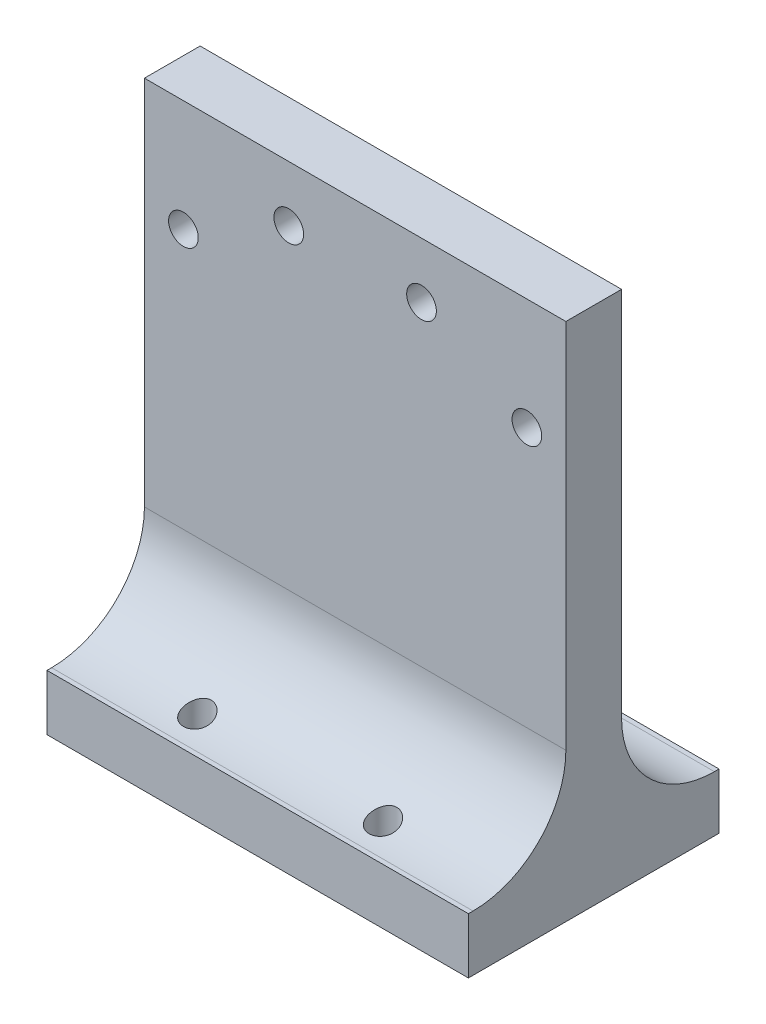
SolidWorks part; units mm, degrees
ref_plane "Płaszczyzna przednia" through (0, 0, 0) normal (0, 0, 1) x (1, 0, 0)
ref_plane "Płaszczyzna górna" through (0, 0, 0) normal (0, 1, 0) x (1, 0, 0)
ref_plane "Płaszczyzna prawa" through (0, 0, 0) normal (1, 0, 0) x (0, 0, -1)
sketch "Sketch1" plane through (0, 0, 0) normal (0, 1, 0) x (1, 0, 0)
  line L1 (0, 0) -> (45.4, 0)
  line L2 (0, 0) -> (0, 27)
  line L3 (0, 27) -> (45.4, 27)
  line L4 (45.4, 0) -> (45.4, 27)
  dimension "D1" = 45.4
  dimension "D2" = 27
extrude "Boss-Extrude1" add sketch "Sketch1" along normal blind 6
sketch "Sketch4" plane through (0, 6, 0) normal (0, 1, 0) x (1, 0, 0)
  line L0 (0, 27) -> (0, 0) construction
  line L1 (0, 16.5) -> (45.4, 16.5)
  line L2 (0, 16.5) -> (0, 10.5)
  line L3 (0, 10.5) -> (45.4, 10.5)
  line L4 (45.4, 16.5) -> (45.4, 10.5)
  line L5 (45.4, 0) -> (45.4, 27) construction
  line L6 (0, 0) -> (45.4, 0) construction
  dimension "D1" = 6
  dimension "D2" = 10.5
extrude "Boss-Extrude2" add sketch "Sketch4" along normal blind 50
fillet "Fillet3" radius 10 2 edges at (22.7, 6, -10.5) (22.7, 6, -16.5)
ref_plane "Plane3" through (0, 16, 0) normal (0, -1, 0) x (-1, 0, 0)
hole_wizard "Ø3.0mm Dowel Hole1" positions "Sketch2" profile "Sketch3" hole size "Ø3.0" standard "ANSI Metric" end condition up to next
sketch "Sketch2" plane through (0, 16, 0) normal (0, 1, 0) x (1, 0, 0)
  point P0 (12.7, 23.5)
  point P2 (32.7, 23.5)
  point P4 (32.7, 3.5)
  point P6 (12.7, 3.5)
  dimension "D1" = 20
  dimension "D2" = 20
  dimension "D3" = 20
sketch "Sketch3" plane through (12.7, 16, -23.5) normal (1, 0, 0) x (0, 0, 1)
  line L0 (0, 0) -> (0, 16)
  line L1 (0, 16) -> (1.5, 16)
  line L2 (1.5, 16) -> (1.5, 0)
  line L5 (1.5, 0) -> (0, 0)
  line L11 (0, -6.35) -> (0, 107.95) construction
  dimension "Thru Hole Dia." = 3
  dimension "Thru Hole Depth" = 16
ref_plane "Plane4" through (22.7, 0, 0) normal (1, 0, 0) x (0, 0, -1)
hole_wizard "Ø3.0mm Dowel Hole2" positions "Sketch6" profile "Sketch7" hole size "Ø3.0" standard "ANSI Metric" end condition up to next
sketch "Sketch6" plane through (0, 0, -16.5) normal (0, 0, -1) x (-1, 0, 0)
  line L2 (-45.4, 56) -> (0, 56) construction
  point P0 (-29.85, 50)
  point P2 (-15.55, 50)
  dimension "D1" = 14.3
  dimension "D3" = 6
sketch "Sketch7" plane through (29.85, 50, -16.5) normal (1, 0, 0) x (0, 1, 0)
  line L0 (0, 0) -> (0, 6)
  line L1 (0, 6) -> (1.6, 6)
  line L2 (1.6, 6) -> (1.6, 0)
  line L5 (1.6, 0) -> (0, 0)
  line L11 (0, -6.35) -> (0, 107.95) construction
  dimension "Thru Hole Dia." = 3.2
  dimension "Thru Hole Depth" = 6
hole_wizard "Ø3.0mm Dowel Hole3" positions "3DSketch1" profile "Sketch8" hole size "Ø3.0" standard "ANSI Metric"
sketch3d "3DSketch1"
  line L0 (0, 56, -16.5) -> (0, 16, -16.5) construction
  line L1 (45.4, 56, -16.5) -> (0, 56, -16.5) construction
  point P0 (30.8985, 51.2086, -15.3558)
  point P1 (41.2, 44, -16.5)
  point P3 (4.2, 44, -16.5)
  dimension "D1" = 37
  dimension "D2" = 4.2
  dimension "D3" = 12
sketch "Sketch8" plane through (4.2, 44, -16.5) normal (1, 0, 0) x (0, 1, 0)
  line L0 (0, 0) -> (0, 16.5)
  line L1 (0, 16.5) -> (1.6, 16.5)
  line L2 (1.6, 16.5) -> (1.6, 0)
  line L5 (1.6, 0) -> (0, 0)
  line L11 (0, -6.35) -> (0, 107.95) construction
  dimension "Thru Hole Dia." = 3.2
  dimension "Thru Hole Depth" = 16.5
